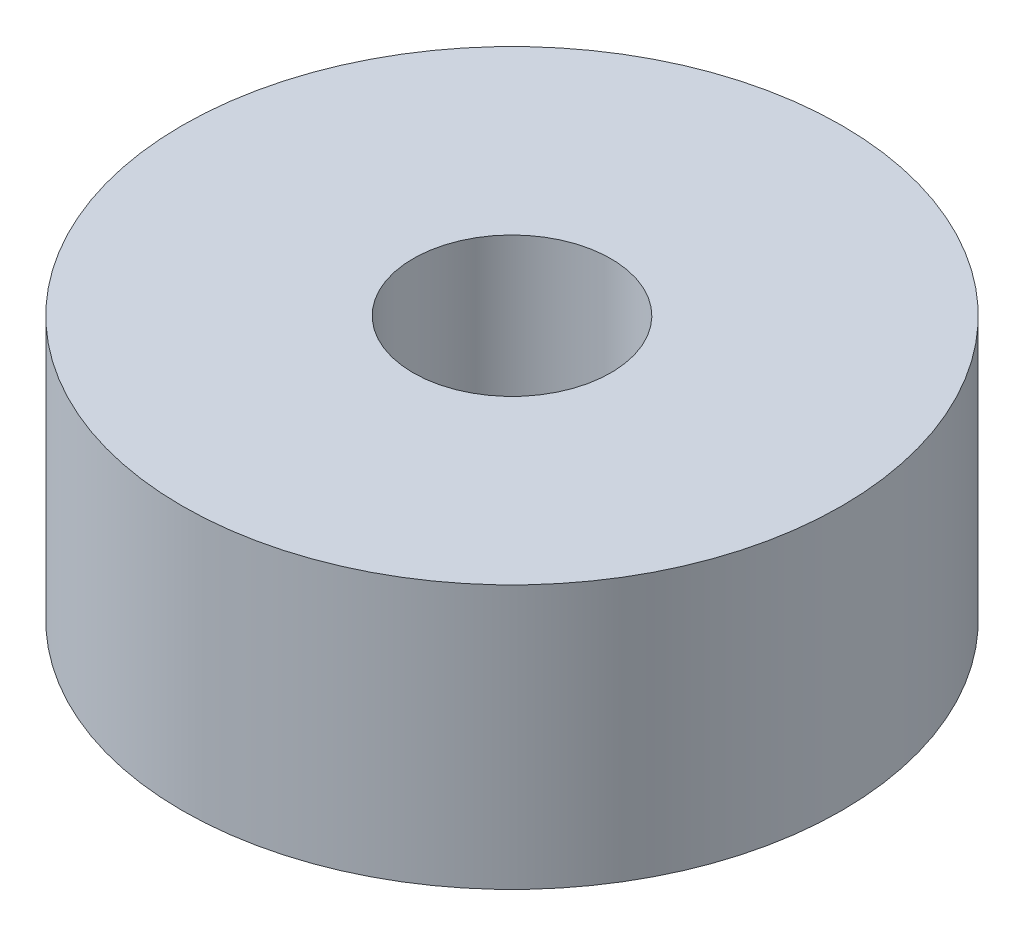
SolidWorks part; units mm, degrees
ref_plane "Front Plane" through (0, 0, 0) normal (0, 0, 1) x (1, 0, 0)
ref_plane "Top Plane" through (0, 0, 0) normal (0, 1, 0) x (1, 0, 0)
ref_plane "Right Plane" through (0, 0, 0) normal (1, 0, 0) x (0, 0, -1)
sketch "Sketch1" plane through (0, 0, 0) normal (0, 1, 0) x (1, 0, 0)
  circle A0 centre (0, 0) radius 1.5
  circle A1 centre (0, 0) radius 5
  dimension "D1" = 3
  dimension "D2" = 10
extrude "Boss-Extrude1" add sketch "Sketch1" along normal blind 4
